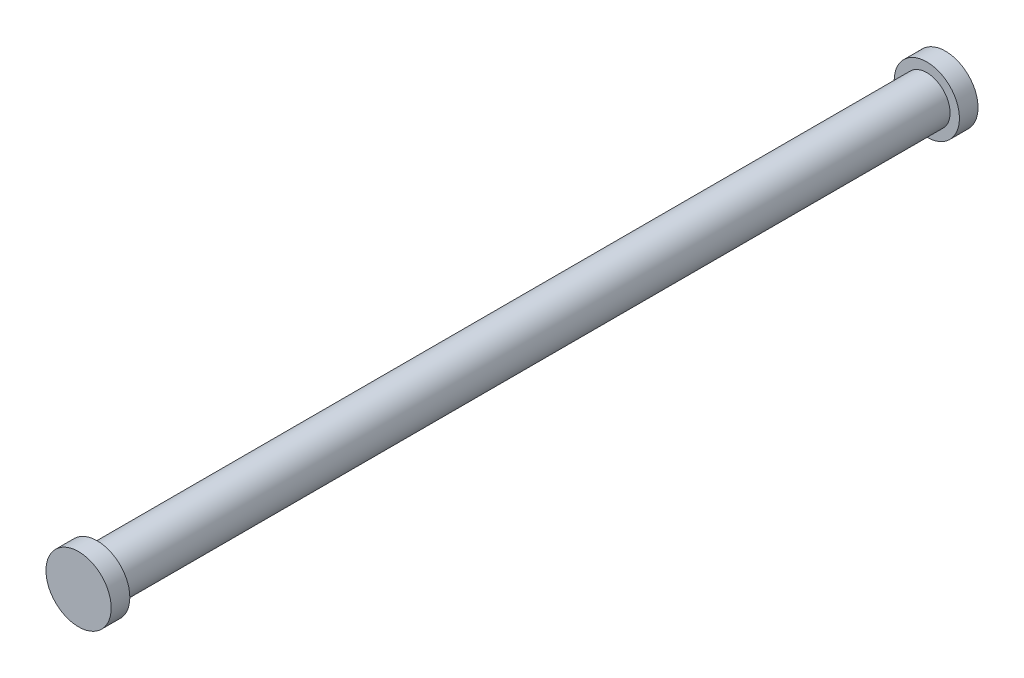
SolidWorks part; units mm, degrees
ref_plane "Front Plane" through (0, 0, 0) normal (0, 0, 1) x (1, 0, 0)
ref_plane "Top Plane" through (0, 0, 0) normal (0, 1, 0) x (1, 0, 0)
ref_plane "Right Plane" through (0, 0, 0) normal (1, 0, 0) x (0, 0, -1)
sketch "Sketch1" plane through (0, 0, 0) normal (0, 0, 1) x (1, 0, 0)
  circle A0 centre (0, 0) radius 2.5
  dimension "D1" = 5
extrude "Boss-Extrude1" add sketch "Sketch1" along normal blind 89
sketch "Sketch2" plane through (0, 0, 0) normal (0, 0, -1) x (-1, 0, 0)
  circle A0 centre (0, 0) radius 3.5
  dimension "D1" = 7
extrude "Boss-Extrude2" add sketch "Sketch2" along normal blind 2
sketch "Sketch3" plane through (0, 0, 89) normal (0, 0, 1) x (1, 0, 0)
  circle A0 centre (0, 0) radius 3.5
  dimension "D1" = 7
extrude "Boss-Extrude3" add sketch "Sketch3" along normal blind 2
